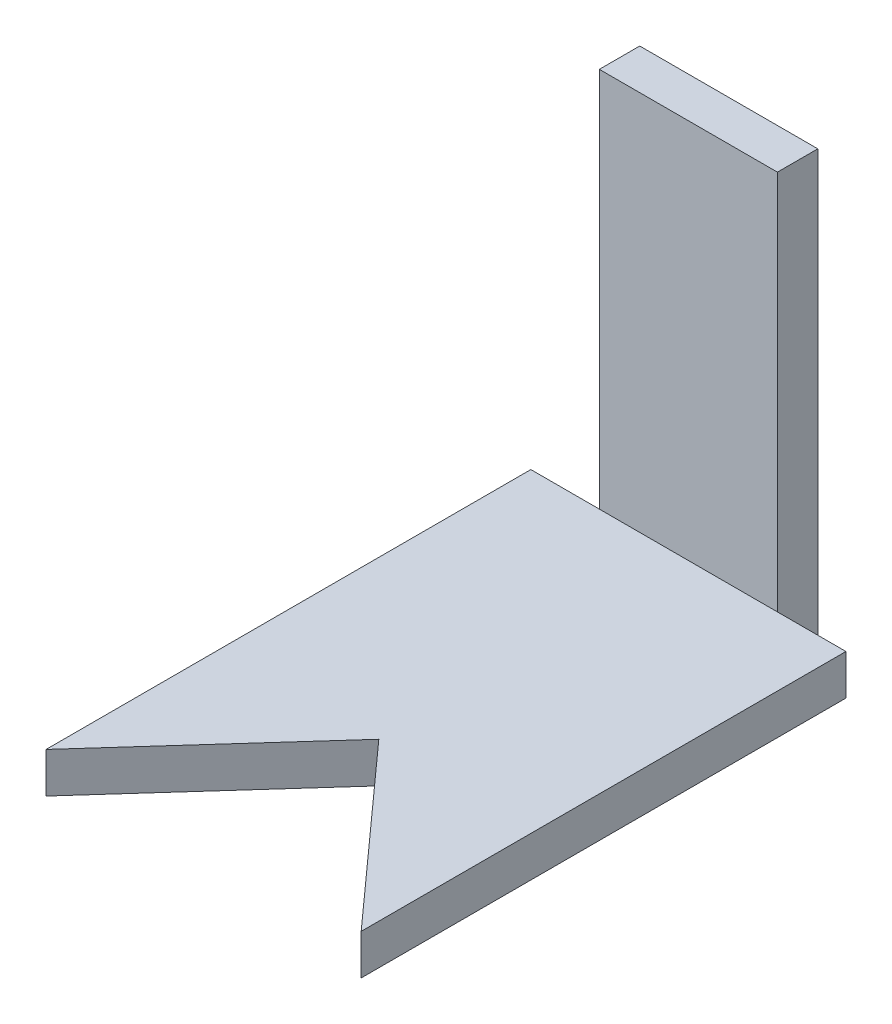
SolidWorks part; units mm, degrees
ref_plane "Front" through (0, 0, 0) normal (0, 0, 1) x (1, 0, 0)
ref_plane "Top" through (0, 0, 0) normal (0, 1, 0) x (1, 0, 0)
ref_plane "Right" through (0, 0, 0) normal (1, 0, 0) x (0, 0, -1)
sketch "Sketch1" plane through (0, 0, 0) normal (0, 0, 1) x (1, 0, 0)
  line L1 (0, 0) -> (27.9908, 0)
  line L2 (0, 0) -> (0, 66.2178)
  line L3 (0, 66.2178) -> (27.9908, 66.2178)
  line L4 (27.9908, 0) -> (27.9908, 66.2178)
  dimension "D1" = 27.9908
  dimension "D2" = 66.2178
extrude "Boss-Extrude1" add sketch "Sketch1" along normal blind 6.35
sketch "Sketch4" plane through (0, 0, 6.35) normal (0, 0, 1) x (1, 0, 0)
  line L0 (13.9954, 66.2178) -> (13.9954, -53.5178) construction
  line L1 (-10.7696, 0) -> (38.7604, 0)
  line L2 (-10.7696, 0) -> (-10.7696, 6.35)
  line L3 (-10.7696, 6.35) -> (38.7604, 6.35)
  line L4 (38.7604, 0) -> (38.7604, 6.35)
  line L6 (27.9908, 66.2178) -> (0, 66.2178) construction
  point P8 (13.9954, 6.35)
  point P9 (14.6194, 66.2178)
  dimension "D1" = 49.53
  dimension "D2" = 6.35
extrude "Boss-Extrude3" add sketch "Sketch4" along normal blind 76.2
sketch "Sketch5" plane through (0, 6.35, 0) normal (0, 1, 0) x (1, 0, 0)
  line L0 (38.7604, -82.55) -> (-10.7696, -82.55) construction
  line L1 (-10.7696, -82.55) -> (-10.7696, -6.35) construction
  line L2 (-10.7696, -82.55) -> (13.9954, -55.0096)
  line L3 (13.9954, -55.0096) -> (38.7604, -82.55)
  line L4 (38.7604, -82.55) -> (-10.7696, -82.55)
  circle A1 centre (13.9954, -71.755) radius 11.1967
  dimension "D2" = 10.795
  dimension "D3" = 24.765
extrude "Cut-Extrude1" cut sketch "Sketch5" against normal through all contours L3 L4 L2
sketch "Sketch6" plane through (0, 6.35, 0) normal (0, 1, 0) x (1, 0, 0)
